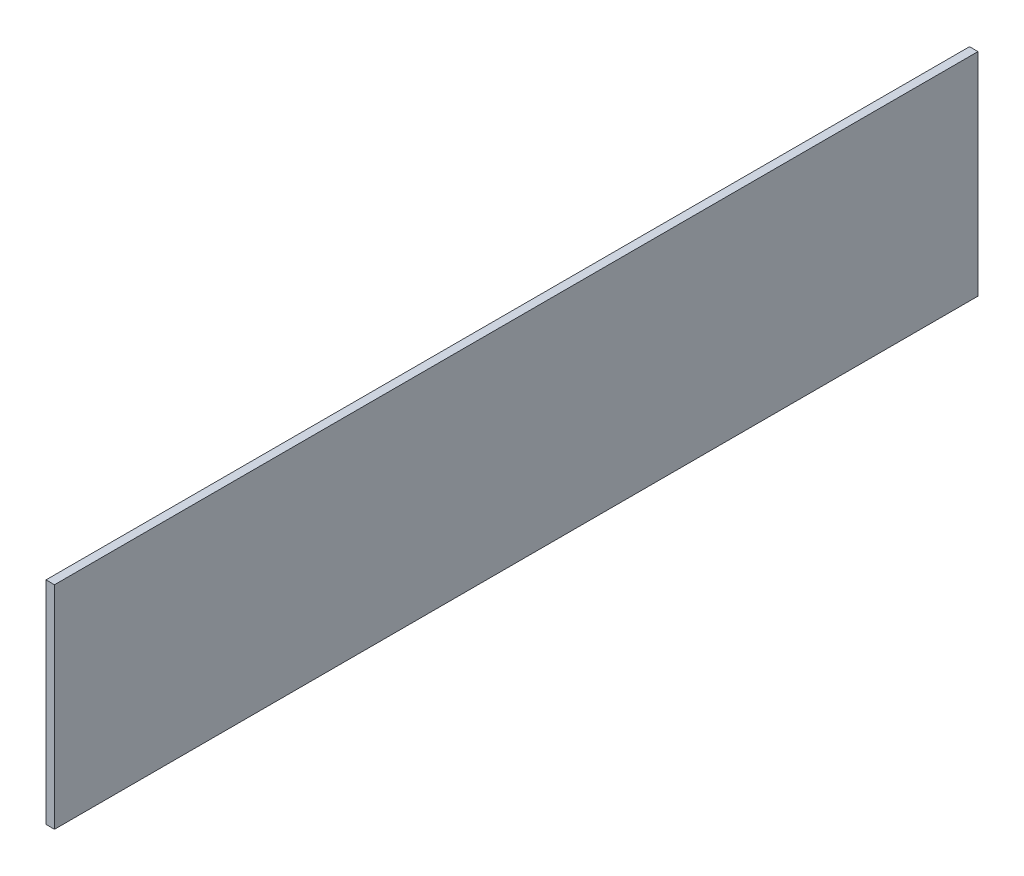
SolidWorks part; units mm, degrees
ref_plane "Front Plane" through (0, 0, 0) normal (0, 0, 1) x (1, 0, 0)
ref_plane "Top Plane" through (0, 0, 0) normal (0, 1, 0) x (1, 0, 0)
ref_plane "Right Plane" through (0, 0, 0) normal (1, 0, 0) x (0, 0, -1)
sketch "Sketch1" plane through (0, 0, 0) normal (1, 0, 0) x (0, 0, -1)
  line L0 (55, 0) -> (-55, 0) construction
  line L1 (-109, 0) -> (109, 0)
  line L2 (-109, 0) -> (-109, 50)
  line L3 (-109, 50) -> (109, 50)
  line L4 (109, 0) -> (109, 50)
  point P6 (0, 0)
  dimension "D1" = 50
  dimension "D2" = 218
extrude "Boss-Extrude1" add sketch "Sketch1" along normal mid plane 2
